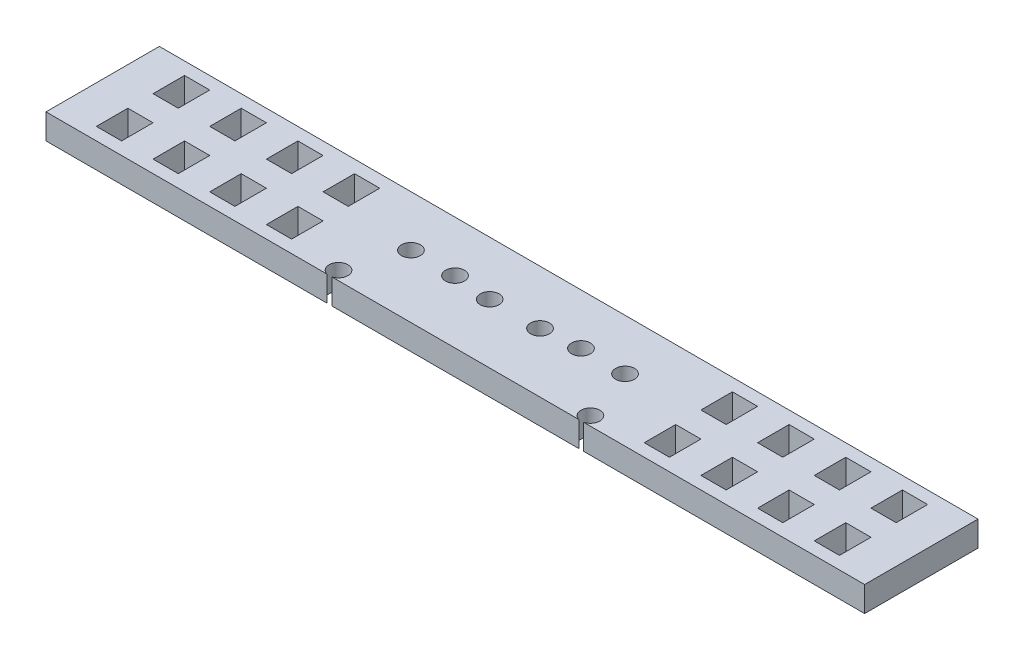
SolidWorks part; units mm, degrees
ref_plane "Front Plane" through (0, 0, 0) normal (0, 0, 1) x (1, 0, 0)
ref_plane "Top Plane" through (0, 0, 0) normal (0, 1, 0) x (1, 0, 0)
ref_plane "Right Plane" through (0, 0, 0) normal (1, 0, 0) x (0, 0, -1)
sketch "Sketch1" plane through (0, 0, 0) normal (0, 1, 0) x (1, 0, 0)
  line L1 (-65, 9) -> (65, 9)
  line L2 (-65, 9) -> (-65, -9)
  line L3 (-65, -9) -> (65, -9)
  line L4 (65, 9) -> (65, -9)
  line L5 (-65, 9) -> (65, -9) construction
  line L6 (-65, -9) -> (65, 9) construction
  point P0 (0, 0)
  dimension "D1" = 18
  dimension "D2" = 130
extrude "Boss-Extrude1" add sketch "Sketch1" along normal blind 4
sketch "Sketch2" plane through (0, 4, 0) normal (0, 1, 0) x (1, 0, 0)
  line L0 (59, -7) -> (59, -2) construction
  line L1 (59, -2) -> (55, -2) construction
  line L2 (55, -2) -> (55, -7) construction
  line L3 (55, -7) -> (59, -7) construction
  line L4 (59, 2) -> (59, 7) construction
  line L5 (59, 7) -> (55, 7) construction
  line L6 (55, 7) -> (55, 2) construction
  line L7 (55, 2) -> (59, 2) construction
  line L8 (-55, -7) -> (-55, -2) construction
  line L9 (-55, -2) -> (-59, -2) construction
  line L10 (-59, -2) -> (-59, -7) construction
  line L11 (-59, -7) -> (-55, -7) construction
  line L12 (-55, 2) -> (-55, 7) construction
  line L13 (-55, 7) -> (-59, 7) construction
  line L14 (-59, 7) -> (-59, 2) construction
  line L15 (-59, 2) -> (-55, 2) construction
  line L16 (59, -7) -> (59, -2)
  line L17 (59, -2) -> (55, -2)
  line L18 (55, -2) -> (55, -7)
  line L19 (55, -7) -> (59, -7)
  line L20 (59, 2) -> (59, 7)
  line L21 (59, 7) -> (55, 7)
  line L22 (55, 7) -> (55, 2)
  line L23 (55, 2) -> (59, 2)
  line L24 (-55, -7) -> (-55, -2)
  line L25 (-55, -2) -> (-59, -2)
  line L26 (-59, -2) -> (-59, -7)
  line L27 (-59, -7) -> (-55, -7)
  line L28 (-55, 2) -> (-55, 7)
  line L29 (-55, 7) -> (-59, 7)
  line L30 (-59, 7) -> (-59, 2)
  line L31 (-59, 2) -> (-55, 2)
  line L32 (46, -2) -> (46, -7)
  line L33 (46, -7) -> (50, -7)
  line L34 (50, -7) -> (50, -2)
  line L35 (50, -2) -> (46, -2)
  line L36 (46, 2) -> (50, 2)
  line L37 (46, 7) -> (46, 2)
  line L38 (50, 2) -> (50, 7)
  line L39 (50, 7) -> (46, 7)
  line L40 (37, -2) -> (37, -7)
  line L41 (37, -7) -> (41, -7)
  line L42 (41, -7) -> (41, -2)
  line L43 (41, -2) -> (37, -2)
  line L44 (37, 2) -> (41, 2)
  line L45 (37, 7) -> (37, 2)
  line L46 (41, 2) -> (41, 7)
  line L47 (41, 7) -> (37, 7)
  line L48 (28, -2) -> (28, -7)
  line L49 (28, -7) -> (32, -7)
  line L50 (32, -7) -> (32, -2)
  line L51 (32, -2) -> (28, -2)
  line L52 (28, 2) -> (32, 2)
  line L53 (28, 7) -> (28, 2)
  line L54 (32, 2) -> (32, 7)
  line L55 (32, 7) -> (28, 7)
  line L56 (0, -9) -> (0, 9) construction
  line L57 (65, 9) -> (-65, 9) construction
  line L58 (-65, -9) -> (65, -9) construction
  line L59 (-50, 7) -> (-46, 7)
  line L60 (-50, 2) -> (-50, 7)
  line L61 (-46, 2) -> (-50, 2)
  line L62 (-32, 7) -> (-28, 7)
  line L63 (-32, 2) -> (-32, 7)
  line L64 (-28, 7) -> (-28, 2)
  line L65 (-28, 2) -> (-32, 2)
  line L66 (-32, -2) -> (-28, -2)
  line L67 (-32, -7) -> (-32, -2)
  line L68 (-28, -7) -> (-32, -7)
  line L69 (-28, -2) -> (-28, -7)
  line L70 (-41, 7) -> (-37, 7)
  line L71 (-41, 2) -> (-41, 7)
  line L72 (-37, 7) -> (-37, 2)
  line L73 (-37, 2) -> (-41, 2)
  line L74 (-41, -2) -> (-37, -2)
  line L75 (-41, -7) -> (-41, -2)
  line L76 (-37, -7) -> (-41, -7)
  line L77 (-37, -2) -> (-37, -7)
  line L78 (-46, 7) -> (-46, 2)
  line L79 (-50, -2) -> (-46, -2)
  line L80 (-50, -7) -> (-50, -2)
  line L81 (-46, -7) -> (-50, -7)
  line L82 (-46, -2) -> (-46, -7)
  point P44 (0, -7.5)
  dimension "D2" = 5
  dimension "D1" = 4
extrude "Cut-Extrude1" cut sketch "Sketch2" against normal through all
sketch "Sketch3" plane through (0, 0, 0) normal (0, -1, 0) x (1, 0, 0)
  circle A1 centre (17, -0.95) radius 1.5
  circle A2 centre (-10, -0.95) radius 1.5
  circle A3 centre (-17, -0.95) radius 1.5
  circle A5 centre (10, -0.95) radius 1.5
  dimension "D1" = 3
extrude "Cut-Extrude2" cut sketch "Sketch3" against normal through all
sketch "Sketch4" plane through (0, 4, 0) normal (0, 1, 0) x (1, 0, 0)
  circle A0 centre (4, 0.45) radius 1.5
  circle A1 centre (-4, 0.45) radius 1.5
  circle A3 centre (-20, -7.55) radius 1.5
  circle A4 centre (20, -7.55) radius 1.5
  dimension "D1" = 3
extrude "Cut-Extrude3" cut sketch "Sketch4" against normal through all
